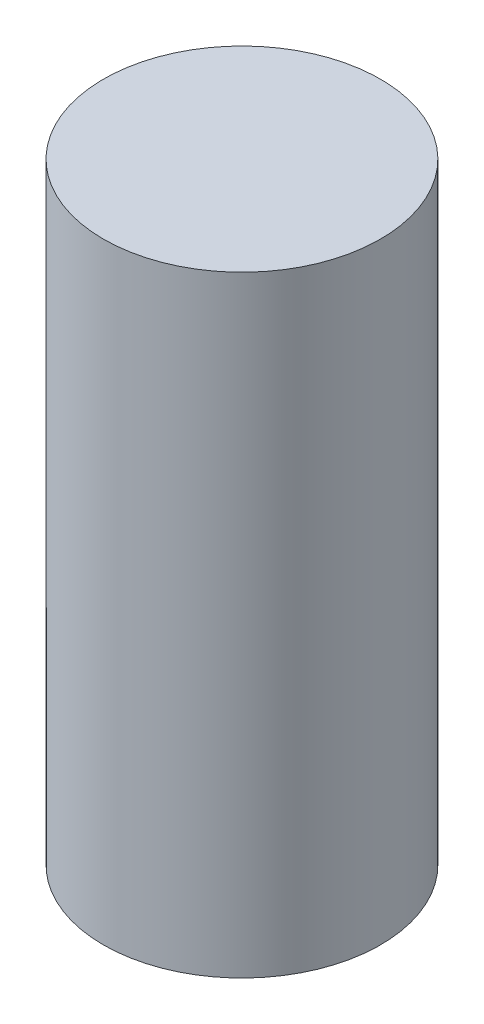
SolidWorks part; units mm, degrees
ref_plane "Front Plane" through (0, 0, 0) normal (0, 0, 1) x (1, 0, 0)
ref_plane "Top Plane" through (0, 0, 0) normal (0, 1, 0) x (1, 0, 0)
ref_plane "Right Plane" through (0, 0, 0) normal (1, 0, 0) x (0, 0, -1)
sketch "Sketch3" plane through (0, 0, 0) normal (0, 1, 0) x (1, 0, 0)
  circle A0 centre (0, 0) radius 68
  dimension "D1" = 136
extrude "Boss-Extrude1" add sketch "Sketch3" along normal blind 300
